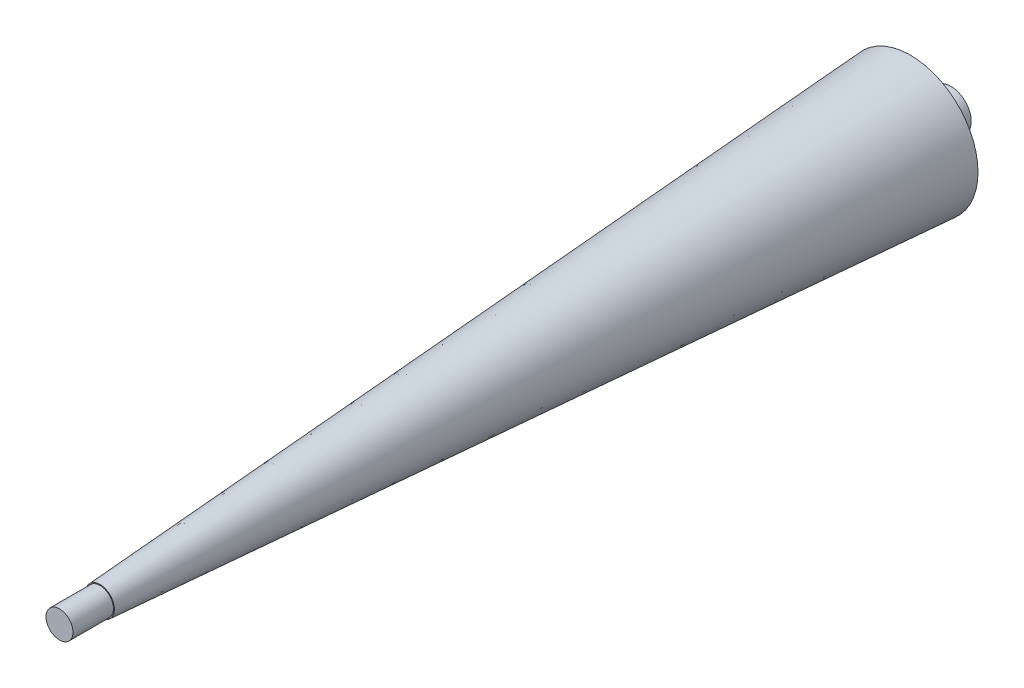
SolidWorks part; units mm, degrees
material "ABS"
ref_plane "Front Plane" through (0, 0, 0) normal (0, 0, 1) x (1, 0, 0)
ref_plane "Top Plane" through (0, 0, 0) normal (0, 1, 0) x (1, 0, 0)
ref_plane "Right Plane" through (0, 0, 0) normal (1, 0, 0) x (0, 0, -1)
sketch "Sketch1" plane through (0, 0, 0) normal (0, 0, 1) x (1, 0, 0)
  circle A0 centre (0, 0) radius 25
  dimension "D1" = 50
extrude "Boss-Extrude1" add sketch "Sketch1" along normal blind 300 draft 3.75
shell "Shell1" thickness 5
sketch "Sketch2" plane through (0, 0, 0) normal (0, 0, -1) x (-1, 0, 0)
  circle A0 centre (0, 0) radius 7.5
  dimension "D1" = 15
extrude "Boss-Extrude2" add sketch "Sketch2" along normal blind 15
sketch "Sketch3" plane through (0, 0, 300) normal (0, 0, 1) x (1, 0, 0)
  circle A0 centre (0, 0) radius 5
  dimension "D1" = 10
extrude "Boss-Extrude3" add sketch "Sketch3" along normal blind 15
